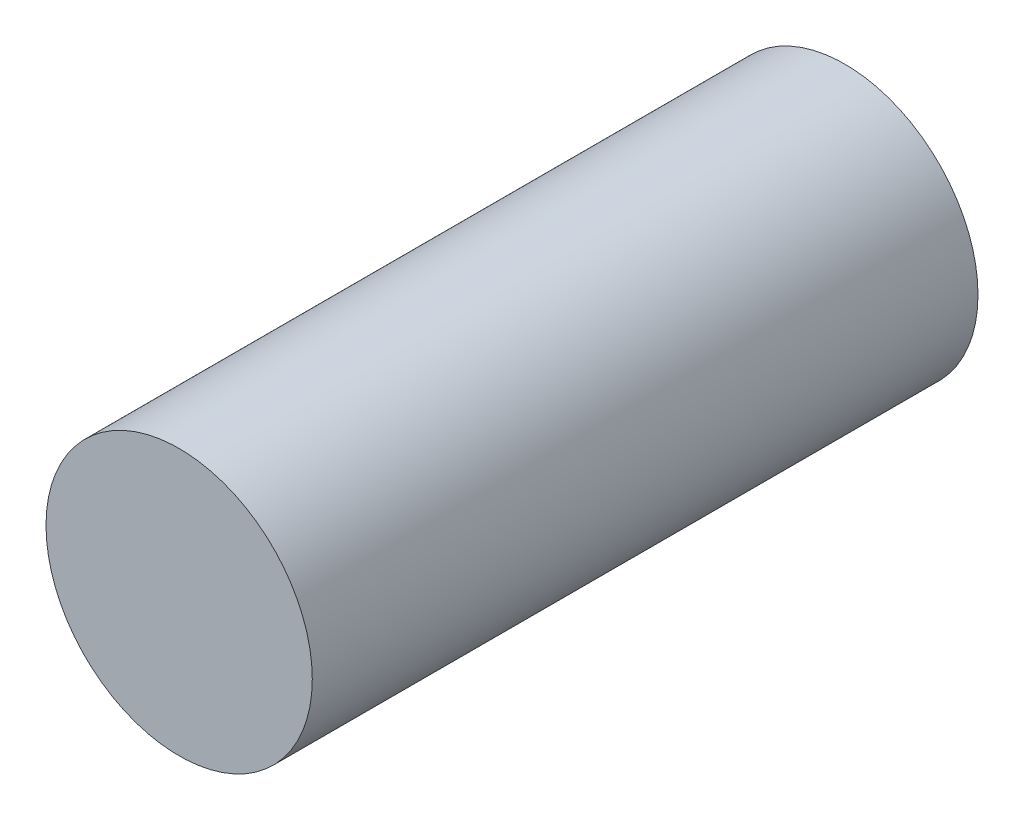
SolidWorks part; units mm, degrees
ref_plane "Front Plane" through (0, 0, 0) normal (0, 0, 1) x (1, 0, 0)
ref_plane "Top Plane" through (0, 0, 0) normal (0, 1, 0) x (1, 0, 0)
ref_plane "Right Plane" through (0, 0, 0) normal (1, 0, 0) x (0, 0, -1)
sketch "Sketch1" plane through (0, 0, 0) normal (0, 0, 1) x (1, 0, 0)
  circle A0 centre (0, 0) radius 3
  dimension "D1" = 6
extrude "Boss-Extrude1" add sketch "Sketch1" along normal blind 15
